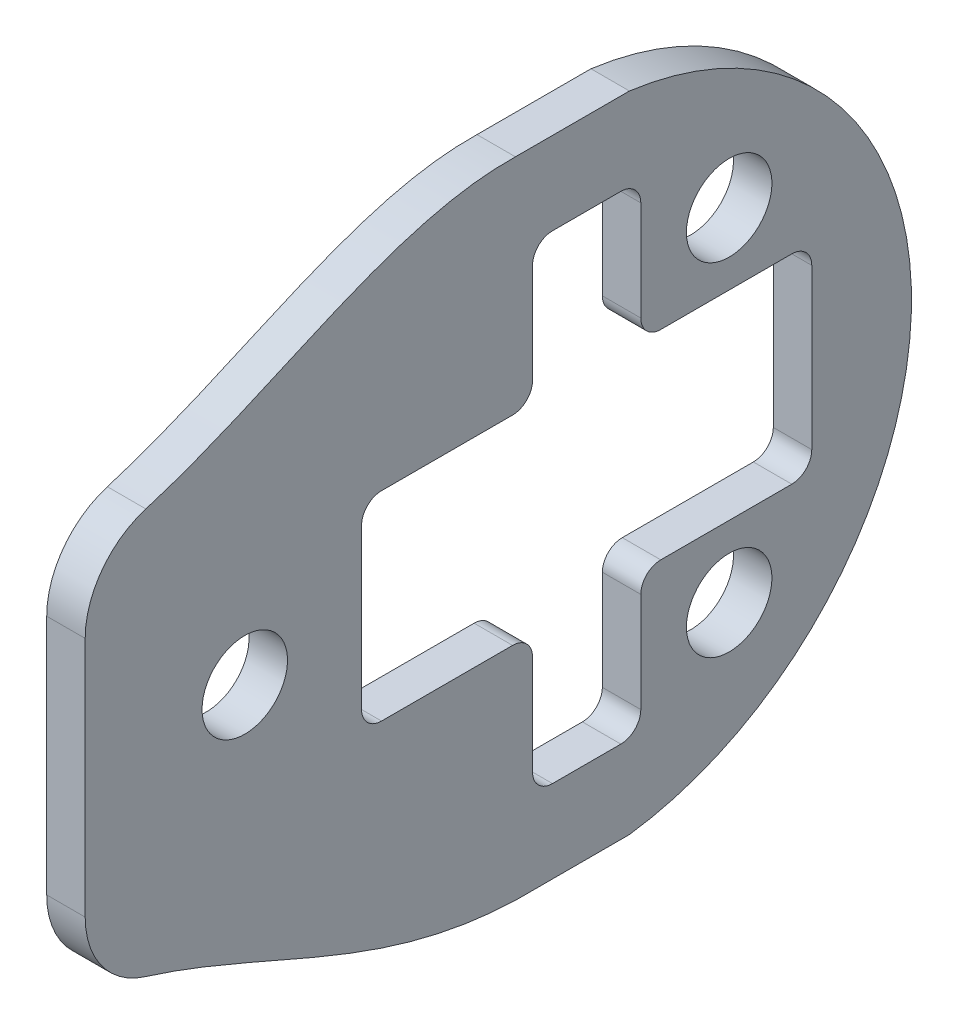
SolidWorks part; units mm, degrees
ref_plane "Piano frontale" through (0, 0, 0) normal (0, 0, 1) x (1, 0, 0)
ref_plane "Piano superiore" through (0, 0, 0) normal (0, 1, 0) x (1, 0, 0)
ref_plane "Piano destro" through (0, 0, 0) normal (1, 0, 0) x (0, 0, -1)
sketch "Schizzo1" plane through (0, 0, 0) normal (1, 0, 0) x (0, 0, -1)
  line L4 (-2.501, -10.3) -> (-2.501, -11.3)
  line L5 (-2.501, -11.3) -> (1.499, -11.3)
  line L7 (1.499, 11.3) -> (-2.501, 11.3)
  line L8 (-2.501, 11.3) -> (-2.501, 10.3)
  line L15 (0, 0) -> (-20.601, 0)
  line L16 (3.245, -3.5) -> (7.899, -3.5)
  line L17 (-7.9, 3.5) -> (2.1, 3.5)
  line L20 (-7.9, 3.5) -> (-7.9, -3.5)
  line L21 (-7.9, -3.5) -> (3.245, -3.5)
  line L30 (-2.501, 10.3) -> (-7.501, 10.3)
  line L31 (-7.501, 10.3) -> (-7.501, 6.3)
  line L35 (-20.601, 6.3) -> (-20.601, -6.3)
  line L37 (-7.501, -6.3) -> (-7.501, -10.3)
  line L38 (-7.501, -10.3) -> (-2.501, -10.3)
  line L40 (7.899, -3.5) -> (7.899, 3.5)
  line L41 (7.899, 3.5) -> (2.1, 3.5)
  line L43 (-1.901, -3.5) -> (1.899, -3.5)
  line L47 (-1.901, -3.5) -> (-1.901, -8.4)
  line L48 (-1.901, -8.4) -> (1.899, -8.4)
  line L49 (1.899, -3.5) -> (1.899, -8.4)
  line L50 (-1.901, 3.5) -> (1.899, 3.5)
  line L51 (-1.901, 3.5) -> (-1.901, 8.4)
  line L52 (-17.601, 6.5611) -> (-17.601, -6.594)
  line L53 (-1.901, 8.4) -> (1.899, 8.4)
  line L54 (1.899, 3.5) -> (1.899, 8.4)
  arc A14 (1.499, 11.3) -> (1.499, -11.3) centre (0, 0) cw
  circle A19 centre (-12, 0) radius 1.5
  circle A20 centre (5, 6) radius 1.5
  circle A21 centre (5, -6) radius 1.5
  spline S0 degree 3 poles (-2.501, 11.3) (-8.3138, 11.4296) (-13.3518, 6.2167) (-20.601, 6.3) knots 0 0 0 0 1 1 1 1
  spline S1 degree 3 poles (-2.501, -11.3) (-9.1647, -11.0636) (-13.4327, -6.3399) (-20.601, -6.3) knots 0 0 0 0 1 1 1 1
  point P7 (-7.9, 0)
  point P17 (11.399, 0)
  point P41 (-20.601, 0)
  dimension "D7" = 11.399
  dimension "D12" = 3.5
  dimension "D14" = 6
  dimension "D15" = 4.9
  dimension "D16" = 3
  dimension "D17" = 3
  dimension "D18" = 3
  dimension "D19" = 4.9
  dimension "D22" = 6
  dimension "D1" = 32
  dimension "D2" = 22.6
  dimension "D3" = 11.3
  dimension "D4" = 1
  dimension "D5" = 1
  dimension "D6" = 4
  dimension "D8" = 7
  dimension "D9" = 5
  dimension "D10" = 3
  dimension "D11" = 12.6
  dimension "D13" = 10
  dimension "D20" = 3.8
  dimension "D21" = 7.9
  dimension "D23" = 6
  dimension "D24" = 12
  dimension "D25" = 5
extrude "Estrusione-Estrusione1" add sketch "Schizzo1" along normal blind 1.35
fillet "Raccordo2" radius 3 1 edges at (0.675, -6.594, 17.601)
fillet "Raccordo3" radius 3 1 edges at (0.675, 6.5611, 17.601)
fillet "Raccordo4" radius 0.7 12 edges at (0.675, 3.5, -7.899) (0.675, 3.5, -1.899) (0.675, 8.4, -1.899) (0.675, 8.4, 1.901) (0.675, 3.5, 1.901) (0.675, -3.5, 1.901) (0.675, -8.4, 1.901) (0.675, -8.4, -1.899) (0.675, -3.5, -7.899) (0.675, -3.5, -1.899) (0.675, -3.5, 7.9) (0.675, 3.5, 7.9)
